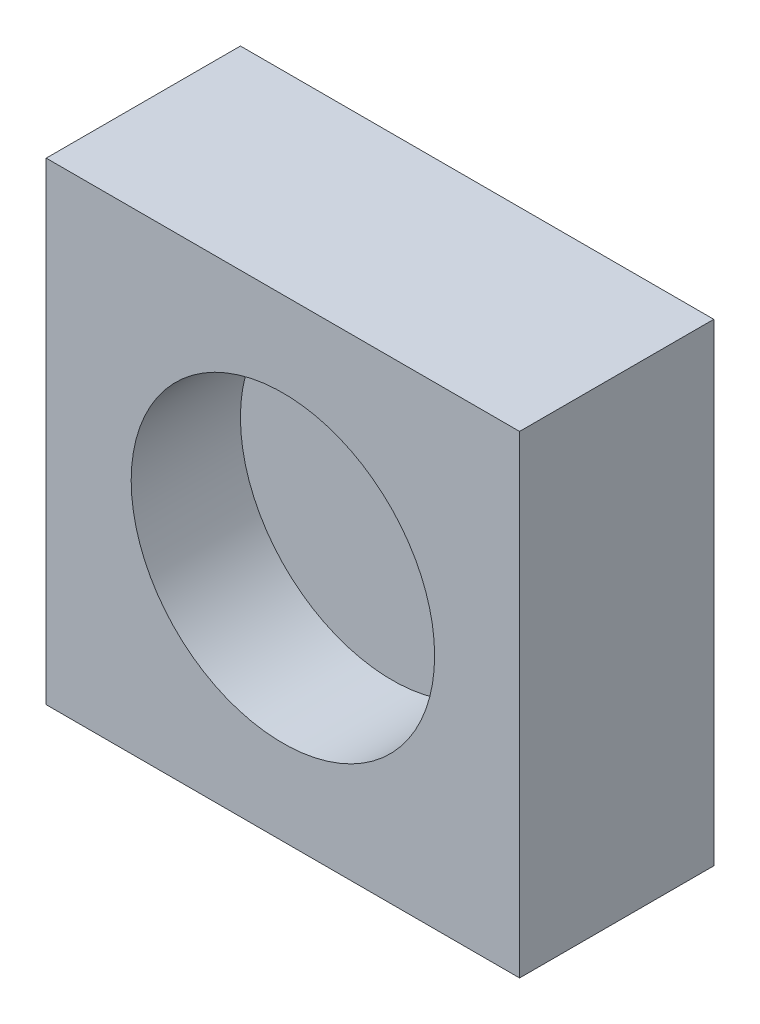
SolidWorks part; units mm, degrees
ref_plane "Спереди" through (0, 0, 0) normal (0, 0, 1) x (1, 0, 0)
ref_plane "Сверху" through (0, 0, 0) normal (0, 1, 0) x (1, 0, 0)
ref_plane "Справа" through (0, 0, 0) normal (1, 0, 0) x (0, 0, -1)
sketch "Эскиз1" plane through (0, 0, 0) normal (0, 0, 1) x (1, 0, 0)
  line L1 (3.9, 3.9) -> (-3.9, 3.9)
  line L2 (3.9, 3.9) -> (3.9, -3.9)
  line L3 (3.9, -3.9) -> (-3.9, -3.9)
  line L4 (-3.9, 3.9) -> (-3.9, -3.9)
  line L5 (3.9, 3.9) -> (-3.9, -3.9) construction
  line L6 (3.9, -3.9) -> (-3.9, 3.9) construction
  point P0 (0, 0)
  dimension "D1" = 7.8
  dimension "D2" = 7.8
extrude "Бобышка-Вытянуть1" add sketch "Эскиз1" along normal blind 3.2
sketch "Эскиз2" plane through (0, 0, 3.2) normal (0, 0, 1) x (1, 0, 0)
  circle A0 centre (0, 0) radius 2.5
extrude "Вырез-Вытянуть1" cut sketch "Эскиз2" against normal blind 1.8
